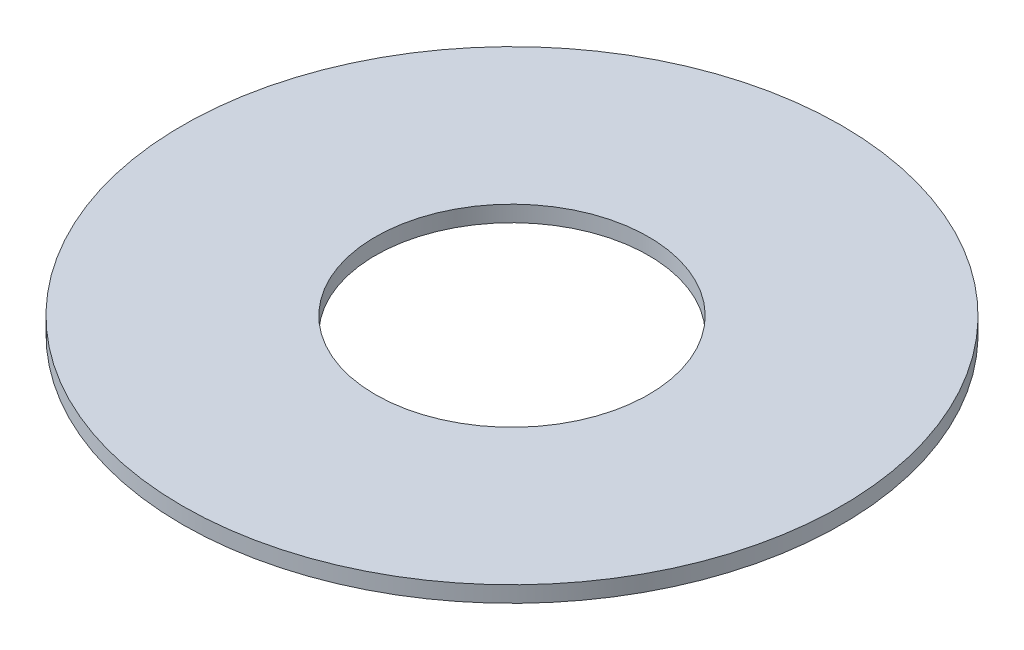
SolidWorks part; units mm, degrees
ref_plane "Front Plane" through (0, 0, 0) normal (0, 0, 1) x (1, 0, 0)
ref_plane "Top Plane" through (0, 0, 0) normal (0, 1, 0) x (1, 0, 0)
ref_plane "Right Plane" through (0, 0, 0) normal (1, 0, 0) x (0, 0, -1)
sketch "Sketch1" plane through (0, 0, 0) normal (0, 1, 0) x (1, 0, 0)
  circle A0 centre (0, 0) radius 41
  circle A1 centre (0, 0) radius 17
  dimension "D1" = 34
  dimension "D2" = 82
extrude "Boss-Extrude1" add sketch "Sketch1" along normal blind 2
